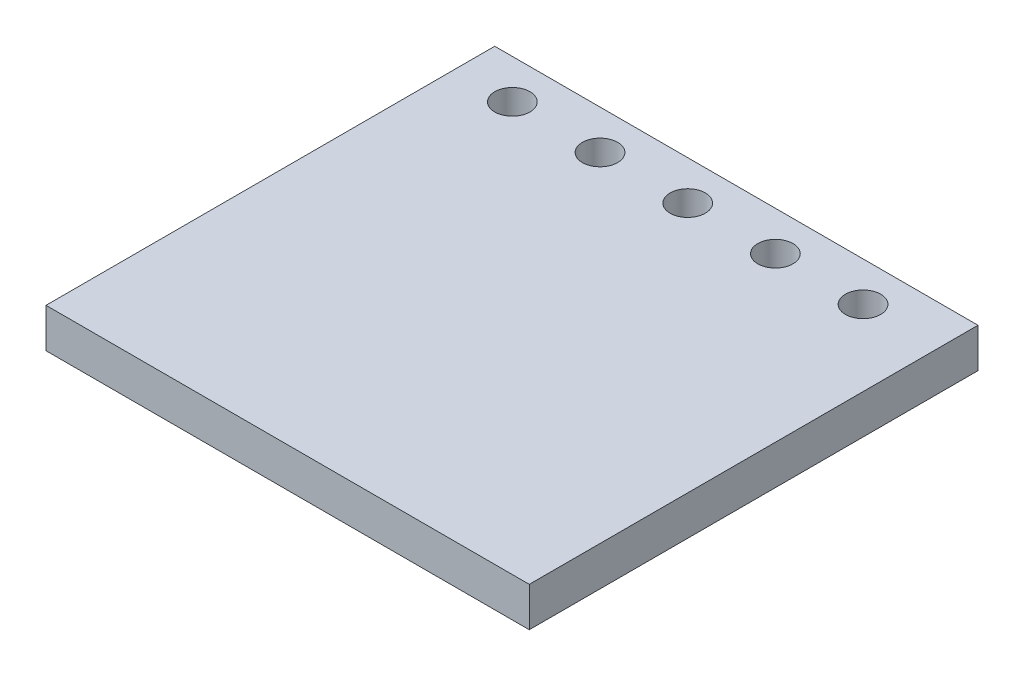
SolidWorks part; units mm, degrees
ref_plane "Front Plane" through (0, 0, 0) normal (0, 0, 1) x (1, 0, 0)
ref_plane "Top Plane" through (0, 0, 0) normal (0, 1, 0) x (1, 0, 0)
ref_plane "Right Plane" through (0, 0, 0) normal (1, 0, 0) x (0, 0, -1)
sketch "Sketch1" plane through (0, 0, 0) normal (0, 1, 0) x (1, 0, 0)
  line L0 (103.6667, 346) -> (354.0297, 328.0438) construction
  line L1 (0, 0) -> (14, 0)
  line L2 (0, 0) -> (0, -13)
  line L3 (0, -13) -> (14, -13)
  line L4 (14, 0) -> (14, -13)
  circle A0 centre (1.65, -1.14) radius 0.51
  circle A1 centre (4.19, -1.14) radius 0.51
  circle A2 centre (6.73, -1.14) radius 0.51
  circle A3 centre (9.27, -1.14) radius 0.51
  circle A4 centre (11.81, -1.14) radius 0.51
  point P5 (1.65, -1.14)
  dimension "D5" = 1.02
  dimension "D1" = 14
  dimension "D2" = 13
  dimension "D3" = 1.14
  dimension "D4" = 1.65
  dimension "D6" = 5
extrude "Boss-Extrude1" add sketch "Sketch1" along normal blind 1.14
